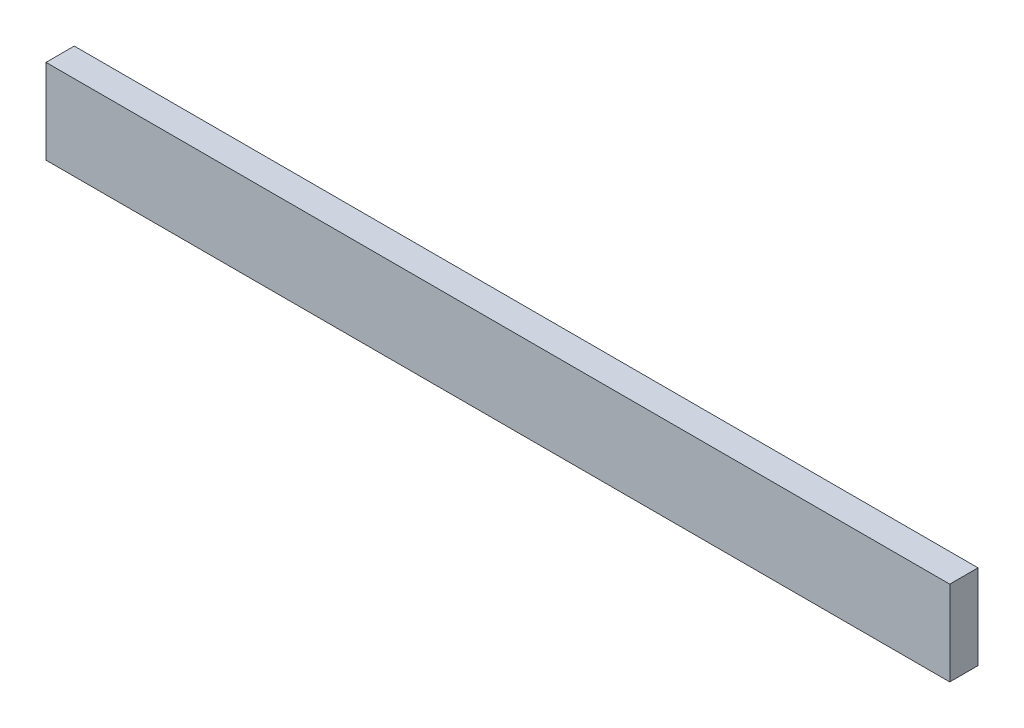
SolidWorks part; units mm, degrees
ref_plane "Front Plane" through (0, 0, 0) normal (0, 0, 1) x (1, 0, 0)
ref_plane "Top Plane" through (0, 0, 0) normal (0, 1, 0) x (1, 0, 0)
ref_plane "Right Plane" through (0, 0, 0) normal (1, 0, 0) x (0, 0, -1)
sketch "Sketch1" plane through (0, 0, 0) normal (0, 0, 1) x (1, 0, 0)
  line L1 (-62.0258, 3.2973) -> (39.5742, 3.2973)
  line L2 (-62.0258, 3.2973) -> (-62.0258, -6.2277)
  line L3 (-62.0258, -6.2277) -> (39.5742, -6.2277)
  line L4 (39.5742, 3.2973) -> (39.5742, -6.2277)
  dimension "D1" = 101.6
  dimension "D2" = 9.525
extrude "Boss-Extrude1" add sketch "Sketch1" along normal blind 3.175
